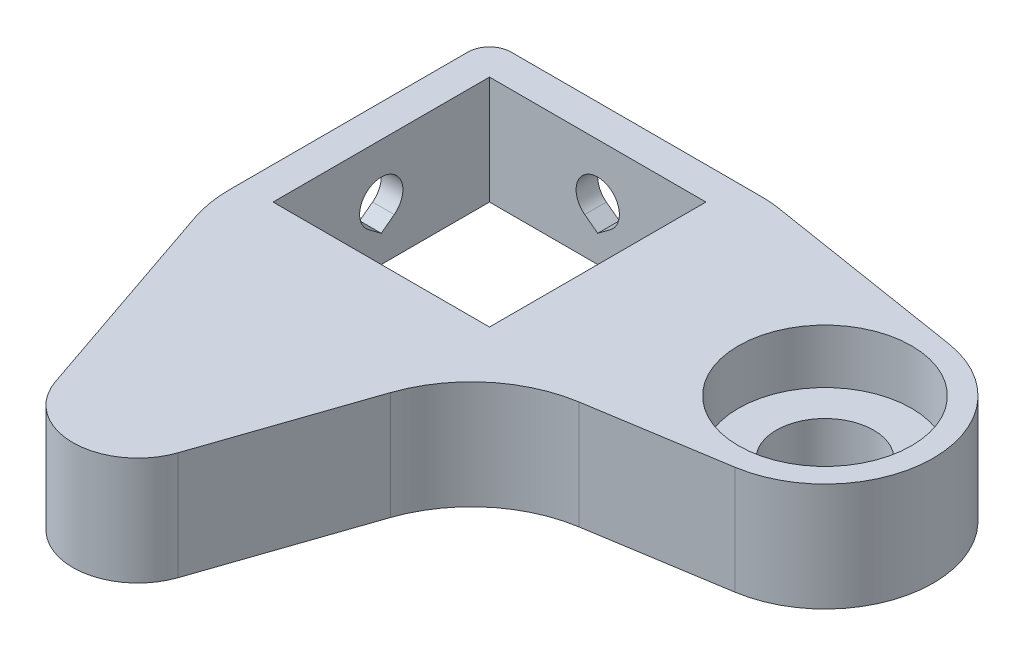
SolidWorks part; units mm, degrees
ref_plane "Front Plane" through (0, 0, 0) normal (0, 0, 1) x (1, 0, 0)
ref_plane "Top Plane" through (0, 0, 0) normal (0, 1, 0) x (1, 0, 0)
ref_plane "Right Plane" through (0, 0, 0) normal (1, 0, 0) x (0, 0, -1)
sketch "Sketch1" plane through (0, 0, 0) normal (0, 1, 0) x (1, 0, 0)
  line L0 (20, 0) -> (41, -10) construction
  line L1 (10, -42.5) -> (0, -20) construction
  line L2 (41, -10) -> (20, -20) construction
  line L3 (0, 0) -> (0, -20) construction
  line L4 (0, 0) -> (20, -20) construction
  line L5 (23.9399, 2.85) -> (42.5764, -0.125)
  line L12 (-3, -23) -> (23, -23) construction
  line L13 (0, 0) -> (20, 0) construction
  line L14 (0, 0) -> (0, -20) construction
  line L15 (0, -20) -> (20, -20) construction
  line L16 (20, 0) -> (20, -20) construction
  line L17 (10, -42.5) -> (20, -20) construction
  line L18 (-3, -21.0074) -> (-3, 1)
  line L19 (-1, 3) -> (22.0482, 3)
  line L20 (23, -23) -> (23, 3) construction
  line L21 (-3, -23) -> (23, 3) construction
  line L22 (-3, 3) -> (23, -23) construction
  line L23 (0, -20) -> (20, -20)
  line L24 (0, -20) -> (0, 0)
  line L25 (0, 0) -> (20, 0)
  line L26 (20, -20) -> (20, 0)
  line L27 (0, -20) -> (20, 0) construction
  line L28 (0, 0) -> (20, -20) construction
  line L29 (30.1306, -21.8617) -> (42.5764, -19.875)
  line L30 (20.6662, -29.8333) -> (15.678, -44.4392)
  line L31 (-2.356, -24.8857) -> (4.322, -44.4392)
  circle A4 centre (10, -42.5) radius 4 construction
  circle A5 centre (41, -10) radius 4 construction
  arc A6 (-3, 1) -> (-1, 3) centre (-1, 1) cw
  circle A7 centre (41, -10) radius 8 construction
  arc A8 (42.5764, -19.875) -> (42.5764, -0.125) centre (41, -10) ccw
  arc A9 (4.322, -44.4392) -> (15.678, -44.4392) centre (10, -42.5) ccw
  arc A10 (30.1306, -21.8617) -> (20.6662, -29.8333) centre (32.0222, -33.7117) ccw
  arc A11 (23.9399, 2.85) -> (22.0482, 3) centre (22.0482, -9) ccw
  arc A12 (-3, -21.0074) -> (-2.356, -24.8857) centre (9, -21.0074) ccw
  point P0 (10, -10)
  point P10 (10, -10)
  dimension "D6" = 8
  dimension "D7" = 16
  dimension "D8" = 20
  dimension "D9" = 12
  dimension "D10" = 12
  dimension "D11" = 12
  dimension "D5" = 2
  dimension "D2" = 20
  dimension "D3" = 3
  dimension "D4" = 42.5
  dimension "D12" = 20
  dimension "D13" = 41
extrude "Boss-Extrude1" add sketch "Sketch1" along normal blind 10
ref_plane "Plane1" through (0, 5, 0) normal (0, 1, 0) x (1, 0, 0)
sketch "Sketch2" plane through (0, 5, 0) normal (0, 1, 0) x (1, 0, 0)
  line L0 (20, 0) -> (41, -10) construction
  line L1 (10, -42.5) -> (0, -20) construction
  line L2 (41, -10) -> (20, -20) construction
  line L3 (0, 0) -> (0, -20) construction
  line L4 (0, 0) -> (20, -20) construction
  line L5 (23.9399, 2.85) -> (42.5764, -0.125) construction
  line L6 (-3, -23) -> (23, -23) construction
  line L7 (0, 0) -> (20, 0) construction
  line L8 (0, 0) -> (0, -20) construction
  line L9 (0, -20) -> (20, -20) construction
  line L10 (20, 0) -> (20, -20) construction
  line L11 (10, -42.5) -> (20, -20) construction
  line L12 (-3, -21.0074) -> (-3, 1) construction
  line L13 (-1, 3) -> (22.0482, 3) construction
  line L14 (23, -23) -> (23, 3) construction
  line L15 (-3, -23) -> (23, 3) construction
  line L16 (-3, 3) -> (23, -23) construction
  line L17 (0, -20) -> (20, -20) construction
  line L18 (0, -20) -> (0, 0) construction
  line L19 (0, 0) -> (20, 0) construction
  line L20 (20, -20) -> (20, 0) construction
  line L21 (0, -20) -> (20, 0) construction
  line L22 (0, 0) -> (20, -20) construction
  line L23 (30.1306, -21.8617) -> (42.5764, -19.875) construction
  line L24 (20.6662, -29.8333) -> (15.678, -44.4392) construction
  line L25 (-2.356, -24.8857) -> (4.322, -44.4392) construction
  circle A0 centre (10, -42.5) radius 4 construction
  circle A1 centre (41, -10) radius 4 construction
  arc A2 (-3, 1) -> (-1, 3) centre (-1, 1) cw construction
  circle A3 centre (41, -10) radius 8
  arc A4 (42.5764, -19.875) -> (42.5764, -0.125) centre (41, -10) ccw construction
  arc A5 (4.322, -44.4392) -> (15.678, -44.4392) centre (10, -42.5) ccw construction
  arc A6 (30.1306, -21.8617) -> (20.6662, -29.8333) centre (32.0222, -33.7117) ccw construction
  arc A7 (23.9399, 2.85) -> (22.0482, 3) centre (22.0482, -9) ccw construction
  arc A8 (-3, -21.0074) -> (-2.356, -24.8857) centre (9, -21.0074) ccw construction
  point P0 (10, -10)
  point P10 (10, -10)
  dimension "D2" = 8
  dimension "D7" = 2
  dimension "D8" = 16
  dimension "D9" = 20
  dimension "D10" = 12
  dimension "D11" = 12
  dimension "D12" = 12
  dimension "D1" = 20
  dimension "D3" = 20
  dimension "D4" = 41
  dimension "D5" = 42.5
  dimension "D6" = 3
extrude "Cut-Extrude2" cut sketch "Sketch2" along normal blind 46
sketch "Sketch3" plane through (0, 5, 0) normal (0, 1, 0) x (1, 0, 0)
  line L0 (20, 0) -> (41, -10) construction
  line L1 (10, -42.5) -> (0, -20) construction
  line L2 (41, -10) -> (20, -20) construction
  line L3 (0, 0) -> (0, -20) construction
  line L4 (0, 0) -> (20, -20) construction
  line L5 (23.9399, 2.85) -> (42.5764, -0.125) construction
  line L6 (-3, -23) -> (23, -23) construction
  line L7 (0, 0) -> (20, 0) construction
  line L8 (0, 0) -> (0, -20) construction
  line L9 (0, -20) -> (20, -20) construction
  line L10 (20, 0) -> (20, -20) construction
  line L11 (10, -42.5) -> (20, -20) construction
  line L12 (-3, -21.0074) -> (-3, 1) construction
  line L13 (-1, 3) -> (22.0482, 3) construction
  line L14 (23, -23) -> (23, 3) construction
  line L15 (-3, -23) -> (23, 3) construction
  line L16 (-3, 3) -> (23, -23) construction
  line L17 (0, -20) -> (20, -20) construction
  line L18 (0, -20) -> (0, 0) construction
  line L19 (0, 0) -> (20, 0) construction
  line L20 (20, -20) -> (20, 0) construction
  line L21 (0, -20) -> (20, 0) construction
  line L22 (0, 0) -> (20, -20) construction
  line L23 (30.1306, -21.8617) -> (42.5764, -19.875) construction
  line L24 (20.6662, -29.8333) -> (15.678, -44.4392) construction
  line L25 (-2.356, -24.8857) -> (4.322, -44.4392) construction
  circle A0 centre (10, -42.5) radius 4
  circle A1 centre (41, -10) radius 4.5
  arc A2 (-3, 1) -> (-1, 3) centre (-1, 1) cw construction
  circle A3 centre (41, -10) radius 8 construction
  arc A4 (42.5764, -19.875) -> (42.5764, -0.125) centre (41, -10) ccw construction
  arc A5 (4.322, -44.4392) -> (15.678, -44.4392) centre (10, -42.5) ccw construction
  arc A6 (30.1306, -21.8617) -> (20.6662, -29.8333) centre (32.0222, -33.7117) ccw construction
  arc A7 (23.9399, 2.85) -> (22.0482, 3) centre (22.0482, -9) ccw construction
  arc A8 (-3, -21.0074) -> (-2.356, -24.8857) centre (9, -21.0074) ccw construction
  point P0 (10, -10)
  point P10 (10, -10)
  dimension "D2" = 8
  dimension "D7" = 2
  dimension "D8" = 16
  dimension "D9" = 20
  dimension "D10" = 12
  dimension "D11" = 12
  dimension "D12" = 12
  dimension "D13" = 9
  dimension "D1" = 20
  dimension "D3" = 20
  dimension "D4" = 41
  dimension "D5" = 42.5
  dimension "D6" = 3
extrude "Cut-Extrude3" cut sketch "Sketch3" against normal blind 10
sketch "Sketch4" plane through (0, 0, -3) normal (0, 0, -1) x (-1, 0, 0)
  line L0 (-20, 10) -> (0, 0) construction
  line L1 (-22.0482, 10) -> (1, 10) construction
  line L2 (-22.0482, 0) -> (1, 0) construction
  line L3 (0, 10) -> (0, 0) construction
  line L4 (-20, 10) -> (-20, 0) construction
sketch "Sketch5" plane through (-3, 0, 0) normal (-1, 0, 0) x (0, 0, 1)
  line L0 (0, 10) -> (20, 0) construction
  line L1 (-1, 10) -> (21.0074, 10) construction
  line L2 (-1, 0) -> (21.0074, 0) construction
  line L3 (0, 10) -> (0, 0) construction
  line L4 (20, 10) -> (20, 0) construction
  point P12 (10, 5)
hole_wizard "CBORE for M5 Hex Head Bolt1" positions "Sketch5" profile "Sketch6" counterbore size "M5" standard "ANSI Metric"
sketch "Sketch6" plane through (-3, 5, 10) normal (0, 1, 0) x (0, 0, 1)
  line L0 (0, 0) -> (0, 10)
  line L1 (0, 10) -> (2, 10)
  line L2 (2, 10) -> (2, 1)
  line L3 (2, 1) -> (3.5, 1)
  line L4 (3.5, 1) -> (3.5, 0)
  line L5 (3.5, 0) -> (0, 0)
  line L10 (0, 10) -> (-2, 10) construction
  line L11 (0, -6.35) -> (0, 107.95) construction
  dimension "Hole Dia." = 4
  dimension "Hole Depth" = 10
  dimension "C'Bore Dia." = 7
  dimension "C'Bore Depth" = 1
  dimension "Drill Angle" = 180
sketch "Sketch7" plane through (0, 0, -3) normal (0, 0, -1) x (-1, 0, 0)
  line L0 (-20, 10) -> (0, 0) construction
  point P0 (-10, 5)
hole_wizard "CBORE for M5 Hex Head Bolt2" positions "Sketch7" profile "Sketch8" counterbore size "M5" standard "ANSI Metric"
sketch "Sketch8" plane through (10, 5, -3) normal (1, 0, 0) x (0, 1, 0)
  line L0 (0, 0) -> (0, 10)
  line L1 (0, 10) -> (2, 10)
  line L2 (2, 10) -> (2, 1)
  line L3 (2, 1) -> (3.5, 1)
  line L4 (3.5, 1) -> (3.5, 0)
  line L5 (3.5, 0) -> (0, 0)
  line L10 (0, 10) -> (-2, 10) construction
  line L11 (0, -6.35) -> (0, 107.95) construction
  dimension "Hole Dia." = 4
  dimension "Hole Depth" = 10
  dimension "C'Bore Dia." = 7
  dimension "C'Bore Depth" = 1
  dimension "Drill Angle" = 180
sketch "Sketch9" plane through (0, 0, -2) normal (0, 0, -1) x (-1, 0, 0)
  line L0 (-20, 10) -> (0, 0) construction
  line L1 (-10, 5) -> (-10, 2.5) construction
  line L2 (-10, 2.5) -> (-8.8, 3.4)
  line L3 (-8.8, 3.4) -> (-11.2, 3.4)
  line L4 (-11.2, 3.4) -> (-10, 2.5)
  circle A0 centre (-10, 5) radius 2 construction
  point P0 (-10, 5)
  dimension "D1" = 2.5
extrude "Cut-Extrude4" cut sketch "Sketch9" against normal up to surface (2 mm away) up to face at (12, 5, 0)
sketch "Sketch10" plane through (0, 0, -2) normal (0, 0, -1) x (-1, 0, 0)
  line L0 (-10, 5) -> (-10, 0.5) construction
  line L1 (-10, 0.5) -> (-7.8001, 2.2778)
  line L2 (-7.8001, 2.2778) -> (-12.1999, 2.2778)
  line L3 (-12.1999, 2.2778) -> (-10, 0.5)
  circle A0 centre (-10, 5) radius 3.5 construction
  circle A1 centre (-10, 5) radius 3.5 construction
  point P0 (-10, 5)
  dimension "D1" = 4.5
extrude "Cut-Extrude5" cut sketch "Sketch10" along normal up to surface (1 mm away) up to face at (6.5, 5, -3)
sketch "Sketch11" plane through (-2, 0, 0) normal (-1, 0, 0) x (0, 0, 1)
  line L1 (10, 5) -> (10, 2.5) construction
  line L2 (10, 2.5) -> (11.2, 3.4)
  line L3 (11.2, 3.4) -> (8.8, 3.4)
  line L4 (8.8, 3.4) -> (10, 2.5)
  line L5 (39.7112, 5) -> (-39.7112, 5) construction
  circle A1 centre (10, 5) radius 2 construction
  point P2 (0, 0)
  point P3 (0, 0)
  point P6 (10, 5)
  point P7 (0, 0)
  point P12 (0, 0)
  point P13 (0, 0)
  point P14 (0, 0)
  point P15 (10.1947, 5.2542)
  point P16 (0, 0)
  point P17 (10, 4.548)
  point P18 (0, 0)
  dimension "D1" = 2.5
extrude "Cut-Extrude6" cut sketch "Sketch11" against normal up to surface (2 mm away) up to face at (0, 5, 8)
sketch "Sketch13" plane through (-2, 0, 0) normal (-1, 0, 0) x (0, 0, 1)
  line L0 (10, 5) -> (10, 0.5) construction
  line L1 (10, 0.5) -> (7.8001, 2.2778)
  line L2 (7.8001, 2.2778) -> (12.1999, 2.2778)
  line L3 (12.1999, 2.2778) -> (10, 0.5)
  circle A0 centre (10, 5) radius 3.5 construction
  circle A1 centre (10, 5) radius 3.5 construction
  point P0 (10, 5)
  dimension "D1" = 4.5
extrude "Cut-Extrude7" cut sketch "Sketch13" against normal up to surface (1 mm away)
